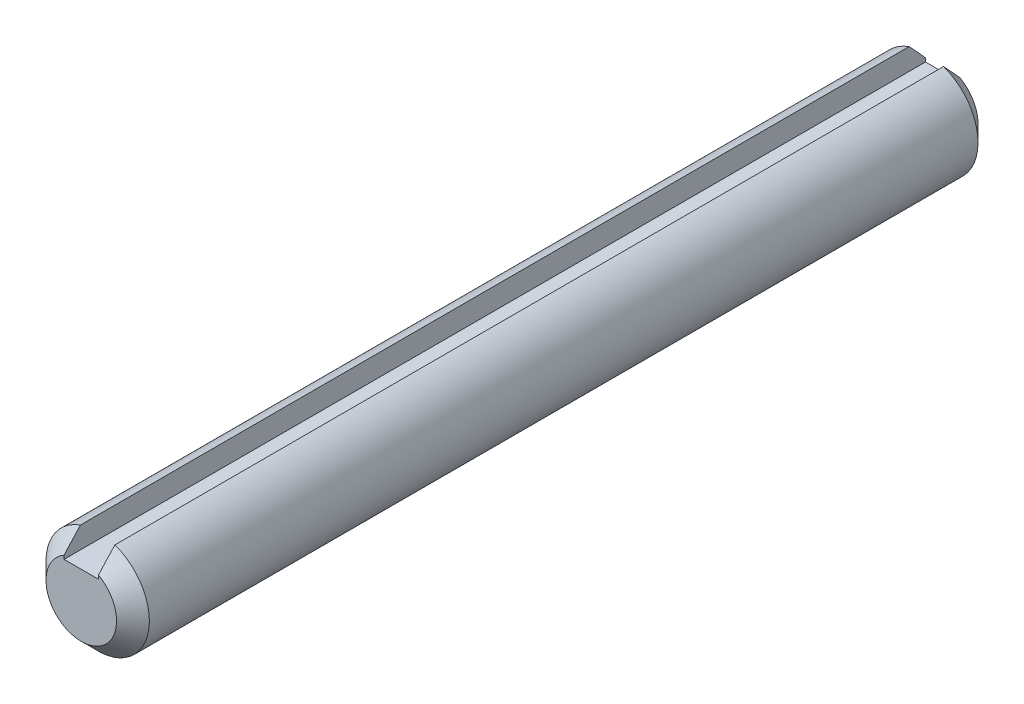
SolidWorks part; units mm, degrees
ref_plane "Front Plane" through (0, 0, 0) normal (0, 0, 1) x (1, 0, 0)
ref_plane "Top Plane" through (0, 0, 0) normal (0, 1, 0) x (1, 0, 0)
ref_plane "Right Plane" through (0, 0, 0) normal (1, 0, 0) x (0, 0, -1)
sketch "Sketch1" plane through (0, 0, 0) normal (1, 0, 0) x (0, 0, -1)
  line L0 (0, 0) -> (0, 6) construction
  line L1 (-150, 6) -> (150, 6)
  line L2 (-150, 6) -> (-150, -6)
  line L3 (-150, -6) -> (150, -6)
  line L4 (150, 6) -> (150, -6)
  line L5 (-150, 6) -> (150, -6) construction
  line L6 (-150, -6) -> (150, 6) construction
  line L7 (0, 0) -> (0, -6) construction
  point P0 (0, 0)
  point P8 (-136.2, 6)
  point P10 (136.2, 6)
  dimension "Diameter" = 12
  dimension "Length" = 300
  dimension "D1" = 13.8
  dimension "D2" = 13.8
sketch "Sketch2" plane through (0, 0, 0) normal (0, 0, 1) x (1, 0, 0)
  line L0 (0, 0) -> (0, 6) construction
  line L2 (2, 3.1569) -> (-2, 3.1569)
  line L3 (2, 3.1569) -> (2, 5.6569)
  line L4 (2, 5.6569) -> (-2, 5.6569)
  line L5 (-2, 3.1569) -> (-2, 5.6569)
  line L6 (2, 3.1569) -> (-2, 5.6569) construction
  line L7 (2, 5.6569) -> (-2, 3.1569) construction
  circle A0 centre (0, 0) radius 6
  point P3 (0, 4.4069)
  dimension "Keyway Width" = 4
  dimension "Keyway Depth" = 2.5
sketch "Sketch3" plane through (0, 0, 0) normal (0, 0, 1) x (1, 0, 0)
  line L1 (-2, 3.1569) -> (-2, 5.6569) construction
  line L2 (2, 3.1569) -> (-2, 3.1569) construction
  line L3 (2, 3.1569) -> (2, 5.6569) construction
  line L5 (-2, 3.1569) -> (-2, 5.6569)
  line L6 (2, 3.1569) -> (-2, 3.1569)
  line L7 (2, 3.1569) -> (2, 5.6569)
  circle A0 centre (0, 0) radius 6 construction
  arc A1 (-2, 5.6569) -> (2, 5.6569) centre (0, 0) ccw
extrude "Boss-Extrude1" add sketch "Sketch3" along normal blind 100
chamfer "Chamfer1" distance 1.905 angle 45 2 edges at (0, -6, 100) (0, -6, 0)
equation "\"D2@Sketch1\"=1.15*\"Diameter@Sketch1\""
equation "\"D1@Sketch1\"=\"D2@Sketch1\""
